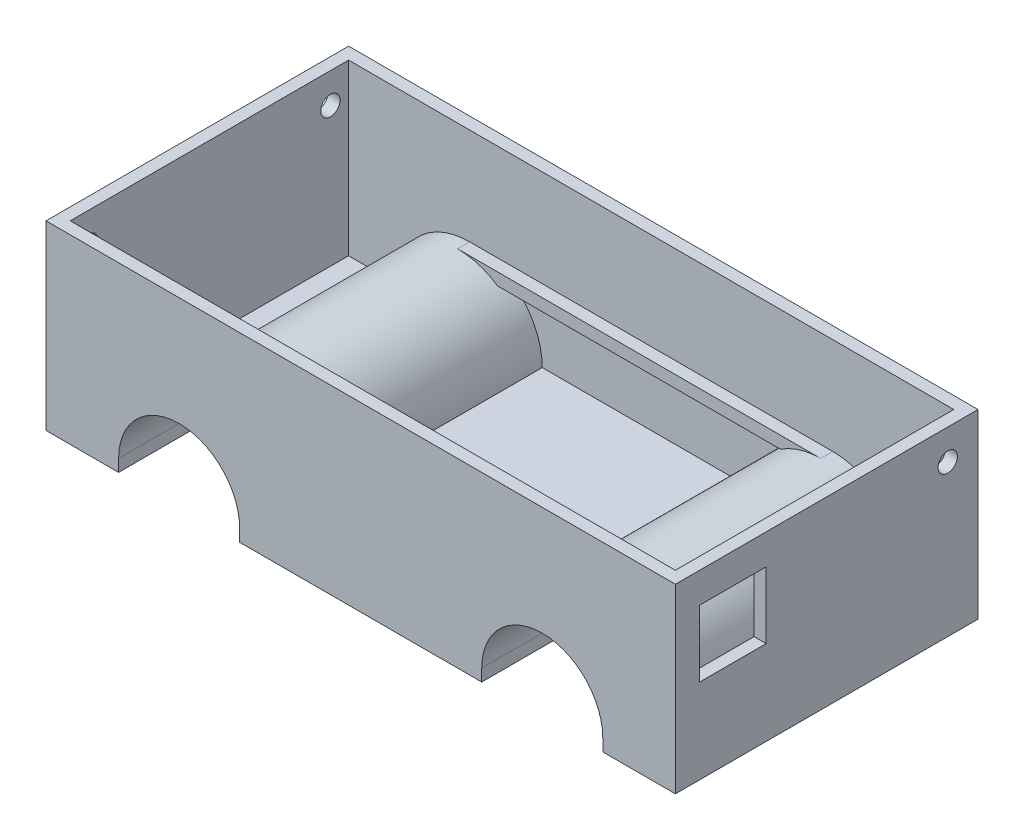
SolidWorks part; units mm, degrees
ref_plane "Ebene vorne" through (0, 0, 0) normal (0, 0, 1) x (1, 0, 0)
ref_plane "Ebene oben" through (0, 0, 0) normal (0, 1, 0) x (1, 0, 0)
ref_plane "Ebene rechts" through (0, 0, 0) normal (1, 0, 0) x (0, 0, -1)
sketch "Skizze1" plane through (0, 0, 0) normal (0, 0, 1) x (1, 0, 0)
  line L0 (37.4016, 0) -> (37.4016, -2)
  line L1 (37.4016, -2) -> (77.4016, -2)
  line L2 (77.4016, -2) -> (77.4016, 0)
  line L3 (75.4016, 0) -> (39.4016, 0)
  line L4 (17.4016, 0) -> (17.4016, -2)
  line L5 (17.4016, -2) -> (5.4016, -2)
  line L6 (5.4016, -2) -> (5.4016, 0)
  line L7 (5.4016, 0) -> (15.4016, 0)
  line L8 (97.4016, 0) -> (97.4016, -2)
  line L9 (97.4016, -2) -> (109.4016, -2)
  line L10 (99.4016, 0) -> (109.4016, 0)
  line L11 (109.4016, 0) -> (109.4016, -2)
  arc A0 (37.4016, 0) -> (17.4016, 0) centre (27.4016, 0) ccw
  arc A1 (97.4016, 0) -> (77.4016, 0) centre (87.4016, 0) ccw
  arc A2 (39.4016, 0) -> (15.4016, 0) centre (27.4016, 0) ccw
  arc A3 (99.4016, 0) -> (75.4016, 0) centre (87.4016, 0) ccw
  dimension "D1" = 12
  dimension "D2" = 10
  dimension "D3" = 12
  dimension "D4" = 10
  dimension "D5" = 12
  dimension "D6" = 40
  dimension "D7" = 2
  dimension "D8" = 2
  dimension "D9" = 2
  dimension "D10" = 2
  dimension "D11" = 2
  dimension "D12" = 2
  dimension "D13" = 12
  dimension "D14" = 2
extrude "Aufsatz-Linear austragen1" add sketch "Skizze1" along normal blind 50
sketch "Skizze3" plane through (0, 0, 0) normal (0, 1, 0) x (1, 0, 0)
  line L0 (109.4016, -50) -> (109.4016, 0) construction
  line L1 (5.4016, 0) -> (109.4016, 0)
  line L2 (5.4016, 0) -> (5.4016, -2)
  line L3 (5.4016, -2) -> (109.4016, -2)
  line L4 (109.4016, 0) -> (109.4016, -2)
  dimension "D1" = 2
extrude "Aufsatz-Linear austragen2" add sketch "Skizze3" along normal blind 28
sketch "Skizze4" plane through (0, 0, 0) normal (0, 1, 0) x (1, 0, 0)
  line L0 (15.4016, -50) -> (5.4016, -50) construction
  line L1 (5.4016, -2) -> (7.4016, -2)
  line L2 (5.4016, -2) -> (5.4016, -50)
  line L3 (5.4016, -50) -> (7.4016, -50)
  line L4 (7.4016, -2) -> (7.4016, -50)
  dimension "D1" = 2
extrude "Aufsatz-Linear austragen3" add sketch "Skizze4" along normal blind 28
sketch "Skizze6" plane through (0, 0, 0) normal (0, 1, 0) x (1, 0, 0)
  line L0 (109.4016, -50) -> (109.4016, -2) construction
  line L1 (7.4016, -50) -> (109.4016, -50)
  line L2 (7.4016, -50) -> (7.4016, -48)
  line L3 (7.4016, -48) -> (109.4016, -48)
  line L4 (109.4016, -50) -> (109.4016, -48)
  dimension "D1" = 2
extrude "Aufsatz-Linear austragen4" add sketch "Skizze6" along normal blind 28
sketch "Skizze7" plane through (0, 0, 0) normal (0, 1, 0) x (1, 0, 0)
  line L0 (99.4016, -2) -> (109.4016, -2) construction
  line L1 (109.4016, -48) -> (107.4016, -48)
  line L2 (109.4016, -48) -> (109.4016, -2)
  line L3 (109.4016, -2) -> (107.4016, -2)
  line L4 (107.4016, -48) -> (107.4016, -2)
  dimension "D1" = 2
extrude "Aufsatz-Linear austragen5" add sketch "Skizze7" along normal blind 28
sketch "Skizze8" plane through (0, 0, 50) normal (0, 0, 1) x (1, 0, 0)
  line L1 (17.4016, 0) -> (37.4016, 0) construction
  line L2 (77.4016, 0) -> (97.4016, 0) construction
  line L3 (77.4016, -2) -> (77.4016, 0) construction
  line L4 (77.4016, 0) -> (97.4016, 0)
  line L5 (17.4016, 0) -> (37.4016, 0)
  arc A2 (37.4016, 0) -> (17.4016, 0) centre (27.4016, 0) ccw
  arc A3 (97.4016, 0) -> (77.4016, 0) centre (87.4016, 0) ccw
extrude "Schnitt-Linear austragen1" cut sketch "Skizze8" against normal through all
sketch "Skizze9" plane through (109.4016, 0, 0) normal (1, 0, 0) x (0, 0, -1)
  line L0 (-50, 28) -> (0, 28) construction
  line L1 (-46, 23) -> (-35, 23)
  line L2 (-46, 23) -> (-46, 12)
  line L3 (-46, 12) -> (-35, 12)
  line L4 (-35, 23) -> (-35, 12)
  line L5 (-50, -2) -> (-50, 28) construction
  dimension "D1" = 11
  dimension "D2" = 11
  dimension "D3" = 5
  dimension "D4" = 4
extrude "Schnitt-Linear austragen2" cut sketch "Skizze9" against normal blind 5
sketch "Skizze10" plane through (0, 0, 48) normal (0, 0, -1) x (-1, 0, 0)
  line L1 (-87.4016, 12) -> (-26.1846, 12)
  line L2 (-87.4016, 12) -> (-87.4016, 10)
  line L3 (-87.4016, 10) -> (-26.1846, 10)
  line L4 (-26.1846, 12) -> (-26.1846, 10)
  arc A0 (-75.4016, 0) -> (-99.4016, 0) centre (-87.4016, 0) ccw construction
  dimension "D1" = 2
extrude "Aufsatz-Linear austragen6" add sketch "Skizze10" along normal blind 2
sketch "Skizze11" plane through (0, 0, 2) normal (0, 0, 1) x (1, 0, 0)
  line L1 (87.4016, 12) -> (27.4016, 12)
  line L2 (87.4016, 12) -> (87.4016, 10)
  line L3 (87.4016, 10) -> (27.4016, 10)
  line L4 (27.4016, 12) -> (27.4016, 10)
  arc A0 (99.4016, 0) -> (75.4016, 0) centre (87.4016, 0) ccw construction
  dimension "D1" = 60
  dimension "D2" = 2
extrude "Aufsatz-Linear austragen7" add sketch "Skizze11" along normal blind 2
sketch "Skizze12" plane through (5.4016, 0, 0) normal (-1, 0, 0) x (0, 0, 1)
  line L0 (0, 28) -> (0, -2) construction
  line L1 (50, 28) -> (50, -2) construction
  line L2 (0, 28) -> (50, 28) construction
  circle A0 centre (5, 23) radius 1.6
  circle A1 centre (45, 23) radius 1.6
  dimension "D1" = 3.2
  dimension "D2" = 3.2
  dimension "D3" = 5
  dimension "D4" = 5
  dimension "D5" = 5
  dimension "D6" = 5
extrude "Schnitt-Linear austragen3" cut sketch "Skizze12" against normal blind 61
sketch "Skizze13" plane through (109.4016, 0, 0) normal (1, 0, 0) x (0, 0, -1)
  line L0 (-50, 28) -> (0, 28) construction
  line L1 (0, -2) -> (0, 28) construction
  circle A0 centre (-5, 23) radius 1.6
  dimension "D1" = 3.2
  dimension "D2" = 5
  dimension "D3" = 5
extrude "Schnitt-Linear austragen4" cut sketch "Skizze13" against normal blind 61
sketch "Skizze14" plane through (5.4016, 0, 0) normal (-1, 0, 0) x (0, 0, 1)
  text T0 "TAXI-GARAGE"
extrude "Schnitt-Linear austragen5" cut sketch "Skizze14" against normal blind 0.5
